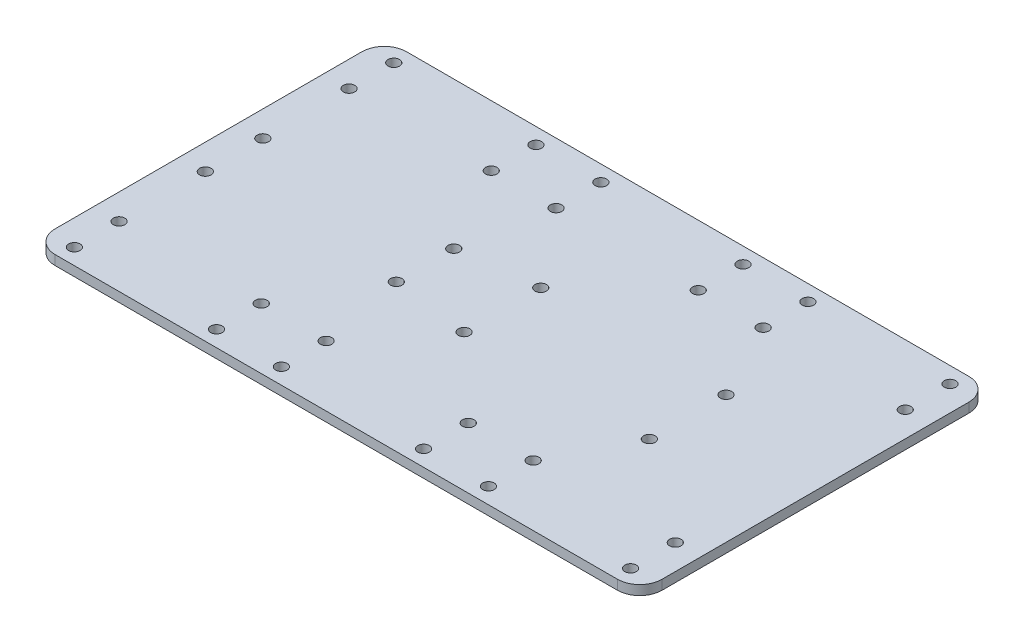
SolidWorks part; units mm, degrees
ref_plane "Front Plane" through (0, 0, 0) normal (0, 0, 1) x (1, 0, 0)
ref_plane "Top Plane" through (0, 0, 0) normal (0, 1, 0) x (1, 0, 0)
ref_plane "Right Plane" through (0, 0, 0) normal (1, 0, 0) x (0, 0, -1)
sketch "Sketch1" plane through (0, 0, 0) normal (0, 1, 0) x (1, 0, 0)
  line L1 (0, 0) -> (190, 0)
  line L2 (0, 0) -> (0, 110)
  line L3 (0, 110) -> (190, 110)
  line L4 (190, 0) -> (190, 110)
  dimension "D1" = 190
  dimension "D2" = 110
extrude "Boss-Extrude1" add sketch "Sketch1" along normal blind 3
hole_wizard "M3 Clearance Hole1" positions "Sketch3" profile "Sketch4" hole size "M3" standard "ANSI Metric" end condition through all
sketch "Sketch3" plane through (0, 3, 0) normal (0, 1, 0) x (1, 0, 0)
  line L1 (190, 110) -> (0, 110) construction
  line L2 (0, 110) -> (0, 0) construction
  line L3 (0, 55) -> (190, 55) construction
  line L4 (190, 0) -> (190, 110) construction
  point P0 (8, 105)
  point P2 (52.5, 105)
  point P4 (52.5, 91)
  point P6 (8, 91)
  point P32 (52.5, 19)
  point P33 (52.5, 5)
  point P34 (8, 19)
  point P35 (8, 5)
  point P45 (72.811, 105)
  point P46 (117.311, 105)
  point P47 (117.311, 91)
  point P48 (72.811, 91)
  point P49 (137.622, 105)
  point P50 (182.122, 105)
  point P51 (182.122, 91)
  point P52 (137.622, 91)
  point P54 (72.811, 19)
  point P55 (117.311, 19)
  point P56 (137.622, 19)
  point P57 (182.122, 19)
  point P58 (182.122, 5)
  point P59 (137.622, 5)
  point P60 (117.311, 5)
  point P61 (72.811, 5)
  point P64 (8, 64)
  point P66 (8, 46)
  point P68 (67.78, 64)
  point P70 (67.78, 46)
  point P72 (92, 67)
  point P74 (92, 43)
  point P76 (150, 43)
  point P78 (150, 67)
  dimension "D1" = 14
  dimension "D2" = 5
  dimension "D3" = 5
  dimension "D4" = 44.5
  dimension "D5" = 8
  dimension "D7" = 20.311
  dimension "D8" = 18
  dimension "D9" = 59.78
  dimension "D10" = 24
  dimension "D11" = 58
  dimension "D12" = 8
  dimension "D13" = 40
  dimension "D14" = 12
  dimension "D15" = 9
  dimension "D6" = 3
sketch "Sketch4" plane through (8, 3, -105) normal (1, 0, 0) x (0, 0, 1)
  line L0 (0, 0) -> (0, 3)
  line L1 (0, 3) -> (1.8, 3)
  line L2 (1.8, 3) -> (1.8, 0)
  line L5 (1.8, 0) -> (0, 0)
  line L11 (0, -6.35) -> (0, 107.95) construction
  dimension "Thru Hole Dia." = 3.6
  dimension "Thru Hole Depth" = 3
fillet "Fillet1" radius 7 4 edges at (190, 1.5, -110) (190, 1.5, 0) (0, 1.5, 0) (0, 1.5, -110)
